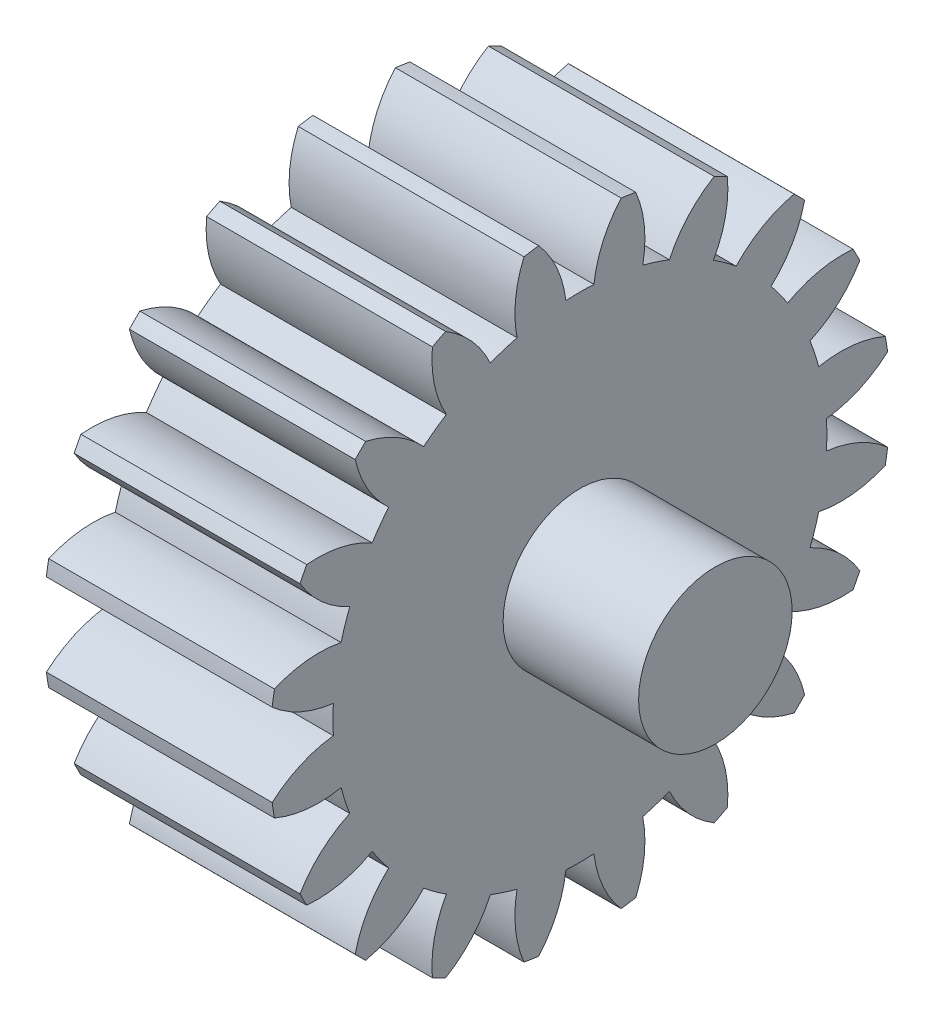
SolidWorks part; units mm, degrees
ref_plane "Plane1" through (0, 0, 0) normal (0, 0, 1) x (1, 0, 0)
ref_plane "Plane2" through (0, 0, 0) normal (0, 1, 0) x (1, 0, 0)
ref_plane "Plane3" through (0, 0, 0) normal (1, 0, 0) x (0, 0, -1)
sketch "HoldingSke" plane through (0, 0, 0) normal (0, 1, 0) x (1, 0, 0)
  line L0 (0, 0) -> (0.7518, -0.2736)
  line L1 (-15, 0) -> (100, 0) construction
  line L2 (0, 0) -> (-2.1039, 2.3779)
  line L3 (0, 0) -> (-11.863, 4.5341)
  line L4 (0, 0) -> (8.1152, 2.9537)
  line L5 (0, 0) -> (-46.8476, -17.4728)
  line L6 (0, 0) -> (-8.2896, -5.593)
  line L7 (-2.1039, 2.3779) -> (8.6586, 51.2059)
  line L8 (-76.2, 54.61) -> (-75.5, 54.61)
  line L9 (-71.009, 38.7566) -> (-53.1078, 45.2721)
  line L10 (-76.2, 71.12) -> (104.1128, 71.12)
  line L11 (0, 0) -> (-10, 0)
  line L12 (-76.2, 101.6) -> (-76.155, 101.6)
  line L13 (24.9733, 27.94) -> (52.9518, 28.4284)
  line L14 (24.9733, 27.94) -> (24.9743, 27.94)
  line L15 (24.9733, 27.94) -> (100.4006, 29.5858)
  line L16 (-63.627, -1.25) -> (-12.827, -1.25)
  circle A0 centre (0, 0) radius 2
  circle A1 centre (0, 0) radius 10.9365
  circle A2 centre (0, 0) radius 37.5
  circle A3 centre (0, 0) radius 2
  dimension "MHD" = 21.873
  dimension "Hub_dia" = 75
  dimension "Bore" = 4
  dimension "MBD" = 4
  dimension "Num_teeth" = 20
  dimension "Pitch" = 0.8
  dimension "Overall_len" = 50
  dimension "Show_teeth" = 20
  dimension "Thickness" = 10
  dimension "OAL" = 50.0001
  dimension "T_dim" = 0.7
  dimension "Ap" = 20
  dimension "H" = 19.05
  dimension "Pitch_radius" = 180.3128
  dimension "Width" = 10
  dimension "Backlash" = 0.045
  dimension "Addendum_fac" = 1
  dimension "Dedendum_fac" = 1.25
  dimension "Clearance_fac" = 0.25
  dimension "Dedendum_add" = 0.001
  dimension "Module" = 1.25
sketch "BasProSke" plane through (0, 0, 0) normal (0, 1, 0) x (1, 0, 0)
  line L0 (-10, 0) -> (60, 0) construction
  line L1 (0, 0) -> (0, 13.75)
  line L2 (0, 0) -> (10, 0)
  line L3 (10, 0) -> (10, 13.75)
  line L4 (10, 13.75) -> (0, 13.75)
  dimension "Thickness" = 10
  dimension "Diameter" = 27.5
revolve "Base-Revolve" add sketch "BasProSke" angle 360 about L0
sketch "TooCutSke" plane through (0, 0, 0) normal (1, 0, 0) x (0, 0, -1)
  line L1 (0, 0) -> (0, 107) construction
  line L2 (0, 0) -> (-1.0594, 12.455) construction
  line L3 (0, 0) -> (-3.9007, 24.6278) construction
  line L4 (-1.0594, 12.455) -> (-1.9503, 12.3139) construction
  arc A0 (0.6211, 10.9188) -> (-0.6211, 10.9188) centre (0, 0) ccw
  arc A1 (1.8466, 13.6511) -> (-1.8466, 13.6511) centre (0, 0) ccw
  circle A2 centre (0, 0) radius 12.5 construction
  circle A3 centre (0, 0) radius 11.7462 construction
  arc A4 (-0.6211, 10.9188) -> (-1.8466, 13.6511) centre (-5.5866, 10.3326) ccw
  arc A5 (1.8466, 13.6511) -> (0.6211, 10.9188) centre (5.5866, 10.3326) ccw
  dimension "Root_dia" = 21.873
  dimension "Overcut_dia" = 27.5508
  dimension "Pitch_dia" = 25
  dimension "Base_dia" = 23.4923
  dimension "Flank_rad" = 5
  dimension "Half_ang" = 9
  dimension "Half_CT" = 0.902
extrude "ToothCut" cut sketch "TooCutSke" along normal through all
fillet "Breaks" [suppressed] radius 0.025
fillet "RootFillets" [suppressed] radius 0.3135
pattern_circular "TeethCuts" count 20 every 18 about axis through (-10, 0, 0) along (1, 0, 0) of "ToothCut", "RootFillets", "Breaks"
sketch "HubNeaOneSke" plane through (0, 0, 0) normal (-1, 0, 0) x (0, 0, 1)
  circle A0 centre (0, 0) radius 10.9365
  dimension "Diameter" = 21.873
extrude "HubNearOne" [suppressed] add sketch "HubNeaOneSke" along normal blind 40.0001
sketch "HubNeaBotSke" plane through (0, 0, 0) normal (-1, 0, 0) x (0, 0, 1)
  circle A0 centre (0, 0) radius 10.9365
  dimension "Diameter" = 21.873
extrude "HubNearBoth" [suppressed] add sketch "HubNeaBotSke" along normal blind 20
ref_plane "FarPln" through (10, 0, 0) normal (1, 0, 0) x (0, 0, -1)
sketch "HubFarSke" plane through (10, 0, 0) normal (1, 0, 0) x (0, 0, -1)
  circle A0 centre (0, 0) radius 10.9365
  dimension "Diameter" = 21.873
extrude "HubFar" [suppressed] add sketch "HubFarSke" along normal blind 20
sketch "BorSke" plane through (0, 0, 0) normal (1, 0, 0) x (0, 0, -1)
  circle A0 centre (0, 0) radius 2
  dimension "Diameter" = 4
extrude "Bore" cut sketch "BorSke" along normal mid plane 100.0001
sketch "KeySke" plane through (0, 0, 0) normal (1, 0, 0) x (0, 0, -1)
  line L0 (-0.8, 0) -> (-0.8, 2.7)
  line L1 (-0.8, 2.7) -> (0.8, 2.7)
  line L2 (0.8, 2.7) -> (0.8, 0)
  line L3 (0, 0) -> (0, 34) construction
  line L4 (-0.8, 0) -> (0.8, 0)
  dimension "Offset" = 2.7
  dimension "Width" = 1.6
extrude "Keyway" [suppressed] cut sketch "KeySke" along normal mid plane 100.0001
pattern_circular "Keyway2" [suppressed] count 2 every 90 about axis through (-10, 0, 0) along (1, 0, 0)
sketch "Sketch1" plane through (10, 0, 0) normal (1, 0, 0) x (0, 0, -1)
sketch "Sketch2" plane through (10, 0, 0) normal (1, 0, 0) x (0, 0, -1)
  circle A0 centre (0, 0) radius 2
extrude "Boss-Extrude1" add sketch "Sketch2" against normal blind 10
sketch "Sketch3" plane through (10, 0, 0) normal (1, 0, 0) x (0, 0, -1)
  circle A0 centre (0, 0) radius 3.4
  dimension "D1" = 6.8
extrude "Boss-Extrude2" add sketch "Sketch3" along normal blind 6
equation "' \"Module@HoldingSke\" = 6.35"
equation "' \"Num_teeth@HoldingSke\" = 12"
equation "' \"Ap@HoldingSke\" =  20"
equation "' \"Ap@HoldingSke\" = 20"
equation "' \"Width@HoldingSke\" = 0.5 * 25.4"
equation "' \"Hub_dia@HoldingSke\"= 1 * 25.4"
equation "' \"Hub_dia@HoldingSke\" = 1 * 25.4"
equation "' \"Overall_len@HoldingSke\" = 1.0 * 25.4"
equation "' \"Bore@HoldingSke\" = 0.75 * 25.4"
equation "' \"T_dim@HoldingSke\" = 0.1 * 25.4"
equation "' \"Width@KeySke\" = 0.25 * 25.4"
equation "' \"Show_teeth@HoldingSke\" = 13"
equation "' \"Backlash@HoldingSke\" = 0.009 * 25.4"
equation "' \"Addendum_fac@HoldingSke\" = 1.0"
equation "' \"Dedendum_fac@HoldingSke\" = 1.25"
equation "' \"Dedendum_add@HoldingSke\" = 0.00005 * 25.4"
equation "' \"Clearance_fac@HoldingSke\" = 0.25"
equation "\"Pitch@HoldingSke\" = 1 / \"Module@HoldingSke\""
equation "\"Overcut_dia@TooCutSke\" = (\"Num_teeth@HoldingSke\" + 2 * \"Addendum_fac@HoldingSke\") / \"Pitch@HoldingSke\" + 0.002 * 25.4"
equation "\"Pitch_dia@TooCutSke\" = \"Num_teeth@HoldingSke\" / \"Pitch@HoldingSke\""
equation "\"Base_dia@TooCutSke\" = \"Num_teeth@HoldingSke\" / \"Pitch@HoldingSke\" * cos((\"Ap@HoldingSke\"  * 3.14159265 / 180))"
equation "\"Root_dia@TooCutSke\" = (\"Num_teeth@HoldingSke\" + 2) / \"Pitch@HoldingSke\" - 2 * (\"Addendum_fac@HoldingSke\" + \"Dedendum_fac@HoldingSke\") / \"Pitch@HoldingSke\" - \"Dedendum_add@HoldingSke\" * 2"
equation "\"Half_ang@TooCutSke\" = 180 / \"Num_teeth@HoldingSke\""
equation "\"Half_CT@TooCutSke\" = \"Num_teeth@HoldingSke\" / \"Pitch@HoldingSke\" * sin((3.14159265 / 2 / \"Num_teeth@HoldingSke\")) / 2 - 7 * \"Backlash@HoldingSke\" / 4"
equation "\"Flank_rad@TooCutSke\" = \"Num_teeth@HoldingSke\" / \"Pitch@HoldingSke\" / 5"
equation "\"Radius@RootFillets\" = \"Clearance_fac@HoldingSke\" / \"Pitch@HoldingSke\" + \"Dedendum_add@HoldingSke\""
equation "\"Break_rad@Breaks\" = 0.02 / \"Pitch@HoldingSke\""
equation "\"Thickness@HoldingSke\" = \"Width@HoldingSke\""
equation "\"OAL@HoldingSke\" = \"Thickness@HoldingSke\""
equation "\"MHD@HoldingSke\" = (\"Num_teeth@HoldingSke\" + 2) / \"Pitch@HoldingSke\" - 2 * (\"Addendum_fac@HoldingSke\" + \"Dedendum_fac@HoldingSke\")  / \"Pitch@HoldingSke\" - \"Dedendum_add@HoldingSke\" * 2"
equation "\"MBD@HoldingSke\" = (\"Num_teeth@HoldingSke\" + 2) / \"Pitch@HoldingSke\" - 2 * (\"Addendum_fac@HoldingSke\" + \"Dedendum_fac@HoldingSke\")  / \"Pitch@HoldingSke\" - \"Dedendum_add@HoldingSke\" * 2 - 0.002 * 25.4"
equation "\"MHD@HoldingSke\" = ((sgn( \"MHD@HoldingSke\" - \"Hub_dia@HoldingSke\" )-1)*( \"MHD@HoldingSke\" - \"Hub_dia@HoldingSke\" ))/-2+ \"Hub_dia@HoldingSke\""
equation "\"MBD@HoldingSke\" = ((sgn( \"MBD@HoldingSke\" - \"Bore@HoldingSke\" )-1)*( \"MBD@HoldingSke\" - \"Bore@HoldingSke\" ))/-2+ \"Bore@HoldingSke\""
equation "\"OAL@HoldingSke\" = ((sgn( \"OAL@HoldingSke\" - \"Overall_len@HoldingSke\" )+1)*( \"OAL@HoldingSke\" - \"Overall_len@HoldingSke\" ))/2 + \"Overall_len@HoldingSke\" + 0.000002 * 25.4"
equation "\"Num_teeth@TeethCuts\" = int( \"Show_teeth@HoldingSke\" ) + 1"
equation "\"Num_teeth@TeethCuts\" = ((sgn( \"Num_teeth@TeethCuts\" - \"Num_teeth@HoldingSke\" )-1)*( \"Num_teeth@TeethCuts\" - \"Num_teeth@HoldingSke\" ))/-2+ \"Num_teeth@HoldingSke\""
equation "\"Num_teeth@TeethCuts\" = ((sgn( \"Num_teeth@TeethCuts\" - 2.0)+1)*( \"Num_teeth@TeethCuts\" - 2.0))/2 +2.0"
equation "\"Angle@TeethCuts\" = 360.0 / \"Num_teeth@HoldingSke\""
equation "\"Diameter@BasProSke\" = (\"Num_teeth@HoldingSke\" + 2 * \"Addendum_fac@HoldingSke\") / \"Pitch@HoldingSke\""
equation "\"Thickness@BasProSke\"  = \"Thickness@HoldingSke\""
equation "' \"Fillet_rad@BasProSke\" =  \"Thickness@HoldingSke\" * 0.05"
equation "' \"Fillet_rad@BasProSke\" = \"Thickness@HoldingSke\" * 0.05"
equation "\"MHD@HoldingSke\" = ((sgn( \"MHD@HoldingSke\" - \"Root_dia@TooCutSke\" )-1)*( \"MHD@HoldingSke\" - \"Root_dia@TooCutSke\" ))/-2+ \"Root_dia@TooCutSke\""
equation "\"Diameter@HubNeaOneSke\" = \"MHD@HoldingSke\""
equation "\"Length@HubNearOne\" = \"OAL@HoldingSke\" - \"Thickness@BasProSke\""
equation "\"Diameter@HubNeaBotSke\" = \"MHD@HoldingSke\""
equation "\"Length@HubNearBoth\" = ( \"OAL@HoldingSke\" - \"Thickness@BasProSke\" ) / 2.0"
equation "\"Thickness@FarPln\" = \"Thickness@BasProSke\""
equation "\"Diameter@HubFarSke\" = \"MHD@HoldingSke\""
equation "\"Length@HubFar\" = ( \"OAL@HoldingSke\" - \"Thickness@BasProSke\" ) / 2.0"
equation "\"Diameter@BorSke\" = \"MBD@HoldingSke\""
equation "\"D1@Bore\" = \"OAL@HoldingSke\" * 2.0"
equation "\"D1@Keyway\" = \"OAL@HoldingSke\" * 2.0"
equation "\"Offset@KeySke\" = \"T_dim@HoldingSke\" + \"MBD@HoldingSke\" / 2.0"
